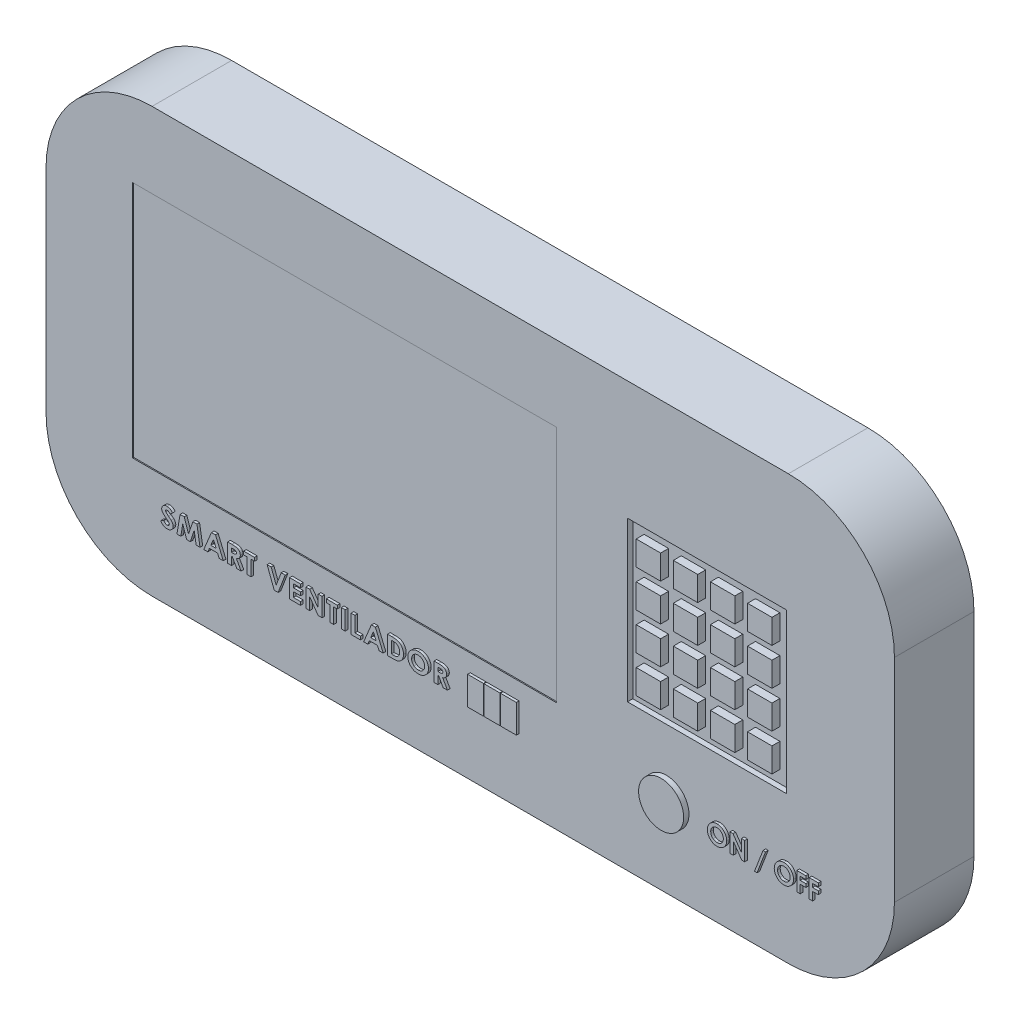
SolidWorks part; units mm, degrees
ref_plane "Alzado" through (0, 0, 0) normal (0, 0, 1) x (1, 0, 0)
ref_plane "Planta" through (0, 0, 0) normal (0, 1, 0) x (1, 0, 0)
ref_plane "Vista lateral" through (0, 0, 0) normal (1, 0, 0) x (0, 0, -1)
sketch "Croquis1" plane through (0, 0, 0) normal (0, 0, 1) x (1, 0, 0)
  line L1 (-60, 40) -> (60, 40)
  line L2 (-80, 20) -> (-80, -20)
  line L3 (-60, -40) -> (60, -40)
  line L4 (80, 20) -> (80, -20)
  line L5 (-80, 40) -> (80, -40) construction
  line L6 (-80, -40) -> (80, 40) construction
  arc A0 (-80, -20) -> (-60, -40) centre (-60, -20) ccw
  arc A1 (60, -40) -> (80, -20) centre (60, -20) ccw
  arc A2 (60, 40) -> (80, 20) centre (60, 20) cw
  arc A3 (-60, 40) -> (-80, 20) centre (-60, 20) ccw
  point P0 (0, 0)
  dimension "D3" = 20
  dimension "D1" = 80
  dimension "D2" = 160
extrude "Saliente-Extruir1" add sketch "Croquis1" along normal blind 15
sketch "Croquis2" plane through (0, 0, 15) normal (0, 0, 1) x (1, 0, 0)
  line L0 (-58, -27) -> (-3, -27) construction
  text T0 "<b>SMART VENTILADOR</b>" font "Century Gothic" height 3.5
  point P3 (-8.713, -27)
  point P5 (-56.6847, -27)
  point P6 (-18.0949, -11.5208)
  dimension "D1" = 27
  dimension "D2" = 55
  dimension "D3" = 3
extrude "Saliente-Extruir2" add sketch "Croquis2" along normal blind 0.5
sketch "Croquis3" plane through (0, 0, 15) normal (0, 0, 1) x (1, 0, 0)
  line L0 (45, -27) -> (68.36, -27) construction
  text T0 "<b>ON / OFF</b>"
  point P3 (67.0486, -27)
  point P4 (58.5964, -27)
  point P8 (68.36, -27)
  dimension "D1" = 45
extrude "Saliente-Extruir3" add sketch "Croquis3" along normal blind 0.5
sketch "Croquis4" plane through (0, 0, 15) normal (0, 0, 1) x (1, 0, 0)
  line L0 (3.1, -22.5) -> (6.1, -22.5)
  line L1 (0, -22.5) -> (3, -22.5)
  line L2 (0, -22.5) -> (0, -27.85)
  line L3 (0, -27.85) -> (3, -27.85)
  line L4 (3, -22.5) -> (3, -27.85)
  line L5 (0, -22.5) -> (3, -27.85) construction
  line L6 (0, -27.85) -> (3, -22.5) construction
  line L7 (3.1, -22.5) -> (3.1, -27.85)
  line L8 (6.1, -22.5) -> (6.1, -27.85)
  line L9 (3.1, -27.85) -> (6.1, -27.85)
  line L10 (6.2, -22.5) -> (9.2, -22.5)
  line L11 (6.2, -22.5) -> (6.2, -27.85)
  line L12 (9.2, -22.5) -> (9.2, -27.85)
  line L13 (6.2, -27.85) -> (9.2, -27.85)
  point P0 (1.5, -25.175)
  dimension "D1" = 3
  dimension "D2" = 5.35
  dimension "D3" = 22.5
  dimension "D4" = 3
  dimension "D6" = 3.1
  dimension "D5" = 3
extrude "Saliente-Extruir4" add sketch "Croquis4" along normal blind 0.5
sketch "Croquis5" plane through (0, 0, 15) normal (0, 0, 1) x (1, 0, 0)
  line L1 (-63.7226, 25.7343) -> (16.2774, 25.7343)
  line L2 (-63.7226, 25.7343) -> (-63.7226, -19.2657)
  line L3 (-63.7226, -19.2657) -> (16.2774, -19.2657)
  line L4 (16.2774, 25.7343) -> (16.2774, -19.2657)
  line L5 (-63.7226, 25.7343) -> (16.2774, -19.2657) construction
  line L6 (-63.7226, -19.2657) -> (16.2774, 25.7343) construction
  point P0 (-23.7226, 3.2343)
  point P5 (-28.3448, 6.3455)
  point P6 (-28.7226, 5.7343)
  point P10 (-23.7226, 3.2343)
  dimension "D1" = 80
  dimension "D2" = 45
  dimension "D3" = 23.7226
  dimension "D4" = 3.2343
extrude "Cortar-Extruir1" cut sketch "Croquis5" against normal blind 0.2
sketch "Croquis6" plane through (0, 0, 15) normal (0, 0, 1) x (1, 0, 0)
  circle A0 centre (37, -25) radius 4.25
  point P5 (35.8807, -23.3906)
  dimension "D1" = 8.5
  dimension "D2" = 37
  dimension "D3" = 25
extrude "Saliente-Extruir5" add sketch "Croquis6" along normal blind 1 contours A0
sketch "Croquis7" plane through (0, 0, 15) normal (0, 0, 1) x (1, 0, 0)
  line L1 (29.6564, 17.5756) -> (59.6564, 17.5756)
  line L2 (29.6564, 17.5756) -> (29.6564, -12.4244)
  line L3 (29.6564, -12.4244) -> (59.6564, -12.4244)
  line L4 (59.6564, 17.5756) -> (59.6564, -12.4244)
  line L5 (29.6564, 17.5756) -> (59.6564, -12.4244) construction
  line L6 (29.6564, -12.4244) -> (59.6564, 17.5756) construction
  point P0 (44.6564, 2.5756)
  point P5 (46.821, 2.7199)
  point P6 (44.6564, 2.5756)
  point P10 (29.6564, -0.2484)
  dimension "D1" = 30
  dimension "D2" = 30
  dimension "D3" = 17.5756
  dimension "D4" = 29.6564
extrude "Cortar-Extruir2" cut sketch "Croquis7" against normal blind 1
sketch "Croquis8" plane through (0, 0, 14) normal (0, 0, 1) x (1, 0, 0)
  line L0 (38.8, 15.5) -> (38.8, 10.9)
  line L5 (31.8, 15.5) -> (36.4, 15.5)
  line L6 (31.8, 15.5) -> (31.8, 10.9)
  line L7 (31.8, 10.9) -> (36.4, 10.9)
  line L8 (36.4, 15.5) -> (36.4, 10.9)
  line L9 (31.8, 15.5) -> (36.4, 10.9) construction
  line L10 (31.8, 10.9) -> (36.4, 15.5) construction
  line L11 (38.8, 15.5) -> (43.4, 15.5)
  line L12 (43.4, 15.5) -> (43.4, 10.9)
  line L13 (38.8, 10.9) -> (43.4, 10.9)
  line L14 (45.8, 15.5) -> (45.8, 10.9)
  line L15 (45.8, 15.5) -> (50.4, 15.5)
  line L16 (50.4, 15.5) -> (50.4, 10.9)
  line L17 (45.8, 10.9) -> (50.4, 10.9)
  line L18 (52.8, 15.5) -> (52.8, 10.9)
  line L19 (52.8, 15.5) -> (57.4, 15.5)
  line L20 (57.4, 15.5) -> (57.4, 10.9)
  line L21 (52.8, 10.9) -> (57.4, 10.9)
  line L22 (38.8, 8.5) -> (38.8, 3.9)
  line L23 (38.8, 8.5) -> (43.4, 8.5)
  line L24 (43.4, 8.5) -> (43.4, 3.9)
  line L25 (38.8, 3.9) -> (43.4, 3.9)
  line L26 (45.8, 8.5) -> (45.8, 3.9)
  line L27 (45.8, 8.5) -> (50.4, 8.5)
  line L28 (50.4, 8.5) -> (50.4, 3.9)
  line L29 (45.8, 3.9) -> (50.4, 3.9)
  line L30 (52.8, 8.5) -> (52.8, 3.9)
  line L31 (52.8, 8.5) -> (57.4, 8.5)
  line L32 (57.4, 8.5) -> (57.4, 3.9)
  line L33 (52.8, 3.9) -> (57.4, 3.9)
  line L34 (38.8, 1.5) -> (38.8, -3.1)
  line L35 (38.8, 1.5) -> (43.4, 1.5)
  line L36 (43.4, 1.5) -> (43.4, -3.1)
  line L37 (38.8, -3.1) -> (43.4, -3.1)
  line L38 (45.8, 1.5) -> (45.8, -3.1)
  line L39 (45.8, 1.5) -> (50.4, 1.5)
  line L40 (50.4, 1.5) -> (50.4, -3.1)
  line L41 (45.8, -3.1) -> (50.4, -3.1)
  line L42 (52.8, 1.5) -> (52.8, -3.1)
  line L43 (52.8, 1.5) -> (57.4, 1.5)
  line L44 (57.4, 1.5) -> (57.4, -3.1)
  line L45 (52.8, -3.1) -> (57.4, -3.1)
  line L46 (38.8, -5.5) -> (38.8, -10.1)
  line L47 (38.8, -5.5) -> (43.4, -5.5)
  line L48 (43.4, -5.5) -> (43.4, -10.1)
  line L49 (38.8, -10.1) -> (43.4, -10.1)
  line L50 (45.8, -5.5) -> (45.8, -10.1)
  line L51 (45.8, -5.5) -> (50.4, -5.5)
  line L52 (50.4, -5.5) -> (50.4, -10.1)
  line L53 (45.8, -10.1) -> (50.4, -10.1)
  line L54 (52.8, -5.5) -> (52.8, -10.1)
  line L55 (52.8, -5.5) -> (57.4, -5.5)
  line L56 (57.4, -5.5) -> (57.4, -10.1)
  line L57 (52.8, -10.1) -> (57.4, -10.1)
  line L58 (31.8, 8.5) -> (31.8, 3.9)
  line L59 (31.8, 8.5) -> (36.4, 8.5)
  line L60 (36.4, 8.5) -> (36.4, 3.9)
  line L61 (31.8, 3.9) -> (36.4, 3.9)
  line L62 (31.8, 1.5) -> (31.8, -3.1)
  line L63 (31.8, 1.5) -> (36.4, 1.5)
  line L64 (36.4, 1.5) -> (36.4, -3.1)
  line L65 (31.8, -3.1) -> (36.4, -3.1)
  line L66 (31.8, -5.5) -> (31.8, -10.1)
  line L67 (31.8, -5.5) -> (36.4, -5.5)
  line L68 (36.4, -5.5) -> (36.4, -10.1)
  line L69 (31.8, -10.1) -> (36.4, -10.1)
  point P0 (34.1, 13.2)
  point P5 (0, 0)
  dimension "D1" = 4.6
  dimension "D2" = 15.5
  dimension "D3" = 31.8
  dimension "D6" = 7
  dimension "D7" = 7
  dimension "D8" = 4.6
  dimension "D4" = 4
  dimension "D5" = 4
extrude "Saliente-Extruir6" add sketch "Croquis8" along normal blind 1.5
